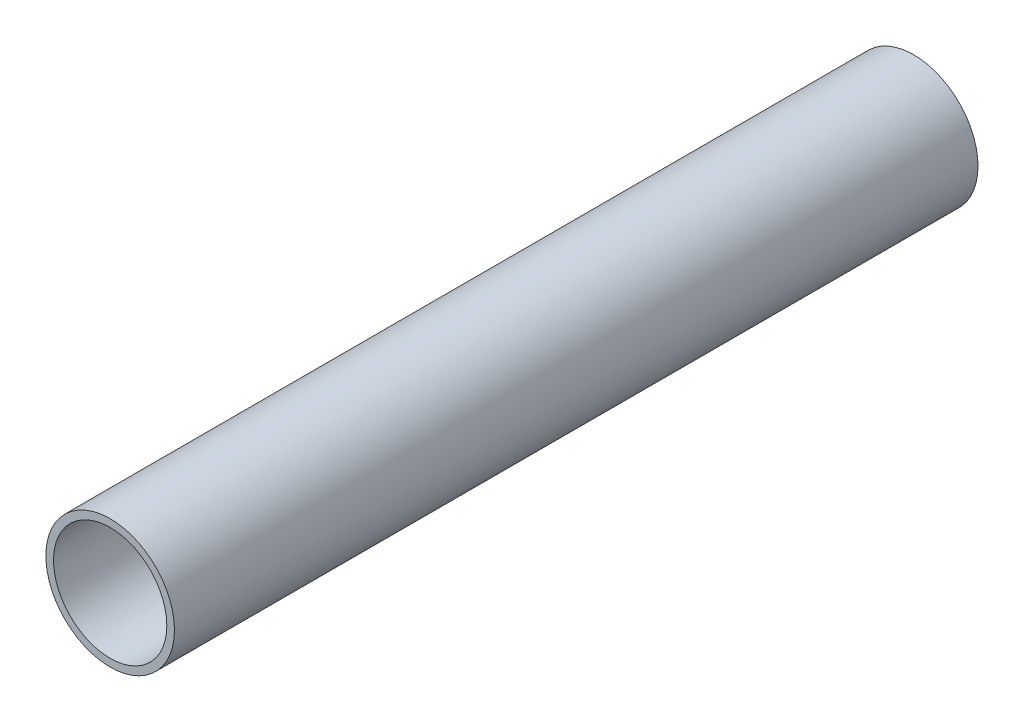
SolidWorks part; units mm, degrees
material "PE Высокой плотности"
ref_plane "Front" through (0, 0, 0) normal (0, 0, 1) x (1, 0, 0)
ref_plane "Top" through (0, 0, 0) normal (0, 1, 0) x (1, 0, 0)
ref_plane "Side" through (0, 0, 0) normal (1, 0, 0) x (0, 0, -1)
sketch "PipeSketch" plane through (0, 0, 0) normal (0, 0, 1) x (1, 0, 0)
  circle A0 centre (0, 0) radius 16
  circle A1 centre (0, 0) radius 14.1
  dimension "OuterDiameter" = 32
  dimension "InnerDiameter" = 28.2
extrude "Extrusion" add sketch "PipeSketch" along normal blind 200
sketch "FilterSketch" plane through (0, 0, 0) normal (0, 0, 1) x (1, 0, 0)
  circle A0 centre (0, 0) radius 16 construction
  dimension "NominalDiameter" = 32
